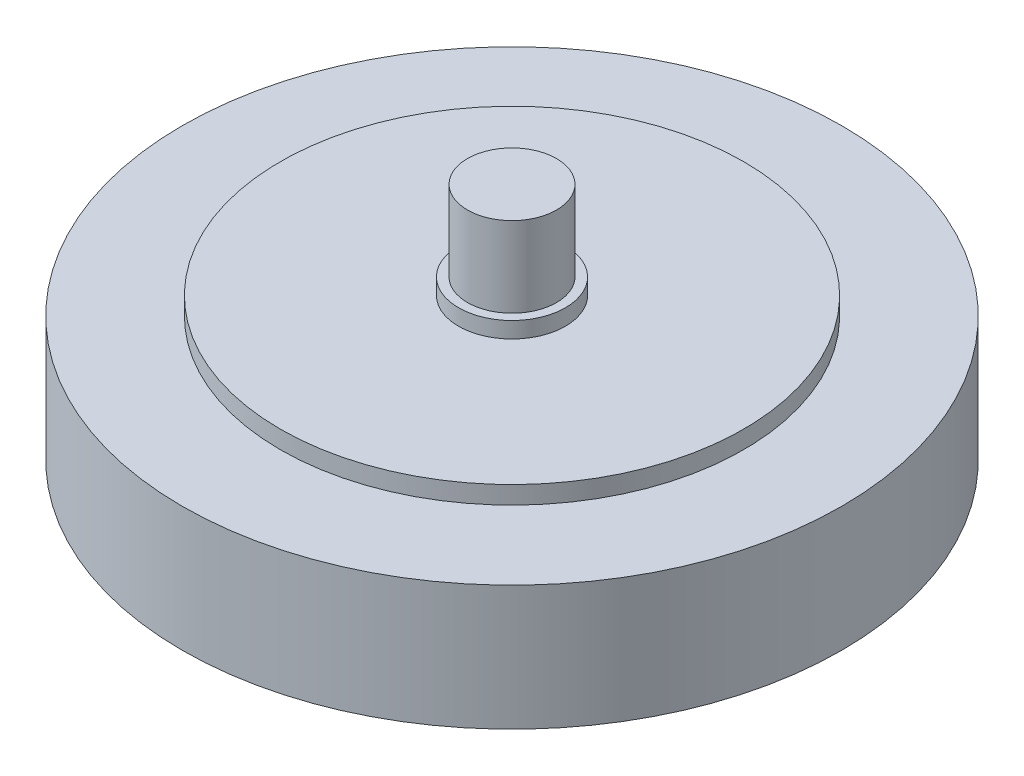
SolidWorks part; units mm, degrees
ref_plane "Front Plane" through (0, 0, 0) normal (0, 0, 1) x (1, 0, 0)
ref_plane "Top Plane" through (0, 0, 0) normal (0, 1, 0) x (1, 0, 0)
ref_plane "Right Plane" through (0, 0, 0) normal (1, 0, 0) x (0, 0, -1)
sketch "Sketch1" plane through (0, 0, 0) normal (0, 0, 1) x (1, 0, 0)
  line L0 (0, 0) -> (18.5, 0)
  line L1 (18.5, 0) -> (18.5, 7)
  line L2 (18.5, 7) -> (13, 7)
  line L3 (13, 7) -> (13, 8)
  line L4 (13, 8) -> (3, 8)
  line L5 (3, 8) -> (3, 8.9)
  line L6 (3, 8.9) -> (2.5, 8.9)
  line L7 (2.5, 8.9) -> (2.5, 13.4)
  line L8 (2.5, 13.4) -> (0, 13.4)
  line L9 (0, 13.4) -> (0, 0)
  line L10 (0, 0) -> (0, 20892.6917) construction
  point P3 (3, 9.0122)
  dimension "D1" = 37
  dimension "D2" = 7
  dimension "D3" = 8
  dimension "D4" = 26
  dimension "D5" = 6
  dimension "D6" = 5
  dimension "D7" = 8.9
  dimension "D8" = 4.5
revolve "Revolve1" add sketch "Sketch1" angle 360 about L10
